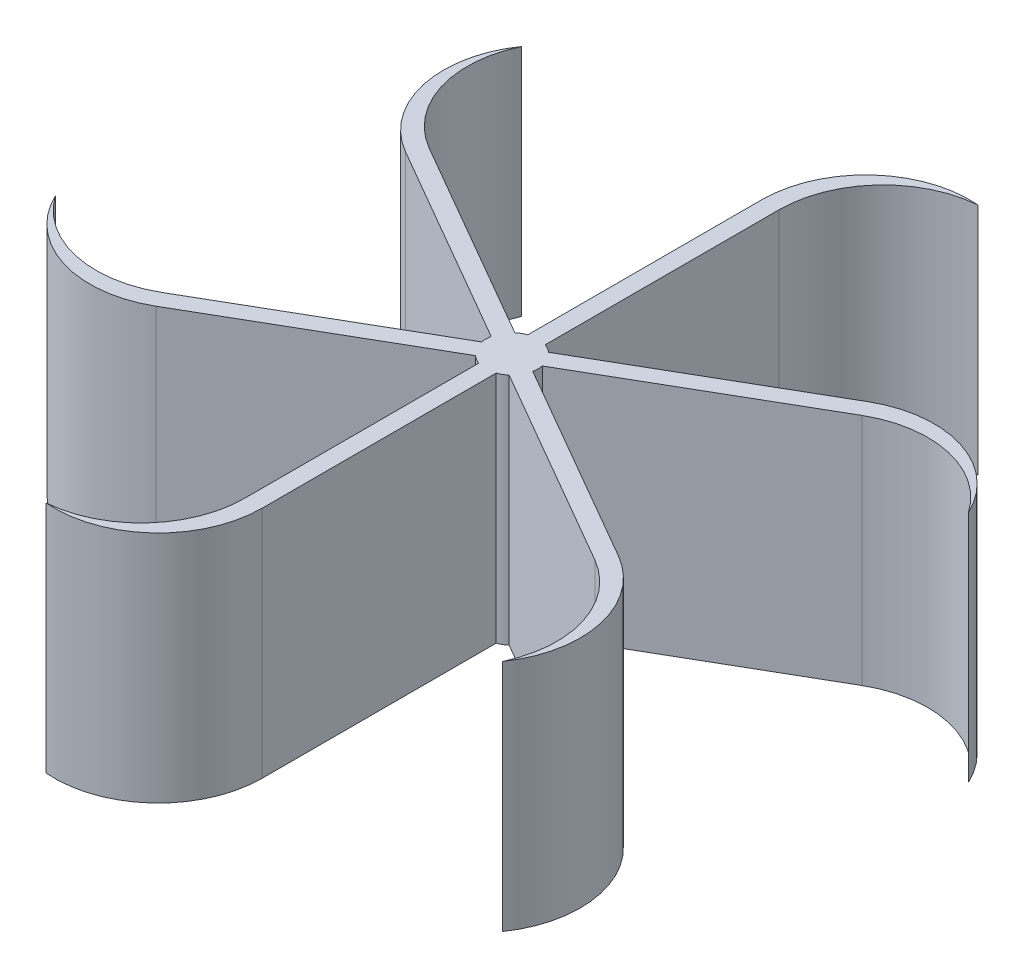
SolidWorks part; units mm, degrees
ref_plane "Front Plane" through (0, 0, 0) normal (0, 0, 1) x (1, 0, 0)
ref_plane "Top Plane" through (0, 0, 0) normal (0, 1, 0) x (1, 0, 0)
ref_plane "Right Plane" through (0, 0, 0) normal (1, 0, 0) x (0, 0, -1)
sketch "Sketch2" plane through (0, 0, 0) normal (0, 1, 0) x (1, 0, 0)
  line L0 (1.9495, 2.2802) -> (25.3322, 15.7802)
  line L1 (-1, 2.8284) -> (-1, 29.8284)
  line L2 (1, 2.8284) -> (1, 29.8284)
  line L3 (2.9495, 0.5482) -> (26.3322, 14.0482)
  line L4 (2.9495, -0.5482) -> (26.3322, -14.0482)
  line L5 (1.9495, -2.2802) -> (25.3322, -15.7802)
  line L6 (1, -2.8284) -> (1, -29.8284)
  line L7 (-1, -2.8284) -> (-1, -29.8284)
  line L8 (-1.9495, -2.2802) -> (-25.3322, -15.7802)
  line L9 (-2.9495, -0.5482) -> (-26.3322, -14.0482)
  line L10 (-2.9495, 0.5482) -> (-26.3322, 14.0482)
  line L11 (-1.9495, 2.2802) -> (-25.3322, 15.7802)
  arc A0 (-1, 29.8284) -> (12, 41.7867) centre (11, 29.8284) cw
  arc A1 (1, 29.8284) -> (12, 41.7867) centre (13, 29.8284) cw
  arc A2 (-1, 2.8284) -> (-1.5, 2.5981) centre (0, 0) ccw
  arc A3 (25.3322, 15.7802) -> (42.1883, 10.501) centre (31.3322, 5.3879) cw
  arc A4 (26.3322, 14.0482) -> (42.1883, 10.501) centre (32.3322, 3.6559) cw
  arc A5 (1.9495, 2.2802) -> (1.5, 2.5981) centre (0, 0) ccw
  arc A6 (3, 0) -> (2.9495, 0.5482) centre (0, 0) ccw
  arc A7 (26.3322, -14.0482) -> (30.1883, -31.2856) centre (20.3322, -24.4405) cw
  arc A8 (25.3322, -15.7802) -> (30.1883, -31.2856) centre (19.3322, -26.1725) cw
  arc A9 (2.9495, -0.5482) -> (3, 0) centre (0, 0) ccw
  arc A10 (1.5, -2.5981) -> (1.9495, -2.2802) centre (0, 0) ccw
  arc A11 (1, -29.8284) -> (-12, -41.7867) centre (-11, -29.8284) cw
  arc A12 (-1, -29.8284) -> (-12, -41.7867) centre (-13, -29.8284) cw
  arc A13 (1, -2.8284) -> (1.5, -2.5981) centre (0, 0) ccw
  arc A14 (-1.5, -2.5981) -> (-1, -2.8284) centre (0, 0) ccw
  arc A15 (-25.3322, -15.7802) -> (-42.1883, -10.501) centre (-31.3322, -5.3879) cw
  arc A16 (-26.3322, -14.0482) -> (-42.1883, -10.501) centre (-32.3322, -3.6559) cw
  arc A17 (-1.9495, -2.2802) -> (-1.5, -2.5981) centre (0, 0) ccw
  arc A18 (-3, 0) -> (-2.9495, -0.5482) centre (0, 0) ccw
  arc A19 (-26.3322, 14.0482) -> (-30.1883, 31.2856) centre (-20.3322, 24.4405) cw
  arc A20 (-25.3322, 15.7802) -> (-30.1883, 31.2856) centre (-19.3322, 26.1725) cw
  arc A21 (-2.9495, 0.5482) -> (-3, 0) centre (0, 0) ccw
  arc A22 (-1.5, 2.5981) -> (-1.9495, 2.2802) centre (0, 0) ccw
  arc A23 (1.5, 2.5981) -> (1, 2.8284) centre (0, 0) ccw
  point P3 (-1.5272, -2.6137)
  point P6 (-1.5, 2.5981)
  point P59 (0, 0)
  dimension "D3" = 12
  dimension "D4" = 12
  dimension "D5" = 6
  dimension "D1" = 2
  dimension "D2" = 27
  dimension "D6" = 1
  dimension "D7" = 6
extrude "Boss-Extrude1" add sketch "Sketch2" along normal blind 27
equation "\"D6@Sketch2\"= \"D1@Sketch2\" / 2"
